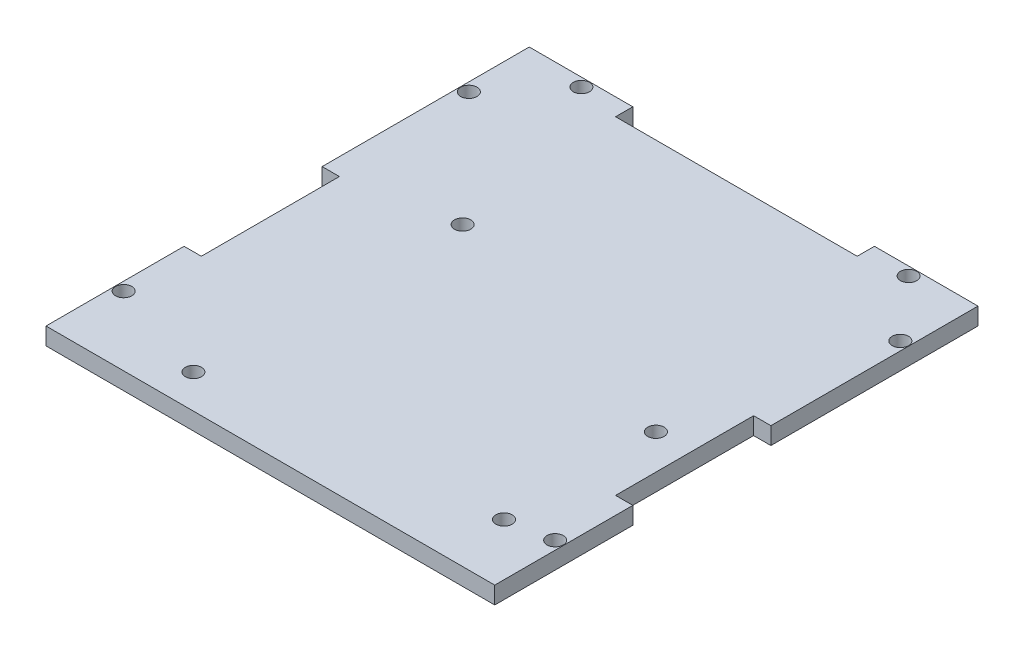
SolidWorks part; units mm, degrees
ref_plane "Front Plane" through (0, 0, 0) normal (0, 0, 1) x (1, 0, 0)
ref_plane "Top Plane" through (0, 0, 0) normal (0, 1, 0) x (1, 0, 0)
ref_plane "Right Plane" through (0, 0, 0) normal (1, 0, 0) x (0, 0, -1)
sketch "Sketch1" plane through (0, 0, 0) normal (0, 1, 0) x (1, 0, 0)
  line L0 (-41.275, 0) -> (-36.3683, -11.7139)
  line L1 (-10.2051, 85.725) -> (10.2051, 85.725)
  line L3 (-41.275, 88.9) -> (-22.225, 88.9)
  line L4 (22.225, 88.9) -> (22.225, 85.725)
  line L5 (41.275, 50.8) -> (41.275, 88.9)
  line L6 (-41.275, 0) -> (-38.1, 0) construction
  line L7 (-41.275, 50.8) -> (-38.1, 50.8)
  line L8 (0, 63.5) -> (0, -63.5) construction
  line L9 (38.1, 50.8) -> (38.1, 25.4)
  line L10 (-38.1, 50.8) -> (-38.1, 25.4)
  line L11 (-41.275, 50.8) -> (-41.275, 88.9)
  line L12 (41.275, 50.8) -> (38.1, 50.8)
  line L13 (-22.225, 88.9) -> (-22.225, 85.725)
  line L14 (-22.225, 85.725) -> (-10.2051, 85.725)
  line L16 (41.275, 88.9) -> (22.225, 88.9)
  line L17 (-41.275, 0) -> (41.275, 0) construction
  line L18 (-38.1, 0) -> (-38.1, 25.4) construction
  line L19 (-38.1, 25.4) -> (-41.275, 25.4)
  line L21 (-41.275, 0) -> (-41.275, 25.4)
  line L22 (38.1, 25.4) -> (41.275, 25.4)
  line L23 (-38.1, 0) -> (-33.467, -10.4244) construction
  line L24 (41.275, 0) -> (41.275, 25.4)
  line L25 (33.467, -10.4244) -> (38.1, 0) construction
  line L26 (-36.3683, -11.7139) -> (-33.467, -10.4244) construction
  line L27 (41.275, 0) -> (36.3683, -11.7139)
  line L28 (36.3683, -11.7139) -> (33.467, -10.4244) construction
  line L29 (-17.858, -45.5446) -> (-12.7, -57.15) construction
  line L30 (-12.7, -57.15) -> (-15.6014, -58.4395) construction
  line L31 (-17.858, -45.5446) -> (-20.7593, -46.8341)
  line L32 (-15.6014, -58.4395) -> (-20.7593, -46.8341)
  line L33 (12.7, -57.15) -> (17.858, -45.5446) construction
  line L34 (-33.467, -10.4244) -> (-17.858, -45.5446)
  line L35 (-12.7, -57.15) -> (12.7, -57.15) construction
  line L36 (17.858, -45.5446) -> (33.467, -10.4244)
  line L38 (41.275, 69.85) -> (-41.275, 69.85) construction
  line L39 (12.7, -57.15) -> (15.6014, -58.4395) construction
  line L40 (17.858, -45.5446) -> (20.7593, -46.8341)
  line L41 (15.6014, -58.4395) -> (20.7593, -46.8341)
  line L42 (38.1, 0) -> (38.1, 25.4) construction
  line L43 (-15.6014, -58.4395) -> (-12.7, -60.325)
  line L44 (-5.08, -57.15) -> (-12.7, -57.15) construction
  line L45 (-5.08, -57.15) -> (-5.08, -60.325)
  line L46 (-5.08, -60.325) -> (-12.7, -60.325)
  line L47 (-12.7, -57.15) -> (-12.7, -60.325) construction
  line L48 (5.08, -57.15) -> (12.7, -57.15) construction
  line L49 (5.08, -57.15) -> (5.08, -60.325)
  line L50 (5.08, -60.325) -> (12.7, -60.325)
  line L51 (12.7, -57.15) -> (12.7, -60.325) construction
  line L52 (15.6014, -58.4395) -> (12.7, -60.325)
  line L53 (-5.08, -57.15) -> (5.08, -57.15)
  line L54 (33.467, -10.4244) -> (36.3683, -11.7139)
  line L55 (-33.467, -10.4244) -> (-36.3683, -11.7139)
  line L56 (10.2051, 85.725) -> (22.225, 85.725)
  point P0 (0, 0)
  point P1 (0, -57.15)
  dimension "D1" = 25.4
  dimension "D2" = 57.15
  dimension "D3" = 3.175
  dimension "D4" = 82.55
  dimension "D5" = 3.175
  dimension "D6" = 44.45
  dimension "D8" = 38.1
  dimension "D9" = 50.8
  dimension "D10" = 25.4
  dimension "D11" = 12.7
  dimension "D12" = 12.7
  dimension "D13" = 10.16
extrude "Boss-Extrude1" add sketch "Sketch1" along normal blind 3.175
sketch "Sketch2" plane through (0, 0, 0) normal (0, -1, 0) x (-1, 0, 0)
  line L0 (39.6875, 50.8) -> (39.6875, 88.9) construction
  line L1 (41.275, 50.8) -> (38.1, 50.8) construction
  line L2 (22.225, 88.9) -> (41.275, 88.9) construction
  line L3 (0, 85.725) -> (0, -57.15) construction
  line L6 (-5.08, -58.7375) -> (-15.1428, -58.7375) construction
  line L7 (5.08, -57.15) -> (-5.08, -57.15) construction
  line L8 (-22.225, 85.725) -> (22.225, 85.725) construction
  line L10 (22.225, 88.9) -> (41.275, 88.9) construction
  line L11 (39.6875, 25.4) -> (39.6875, -3.7899) construction
  line L12 (38.1, 25.4) -> (41.275, 25.4) construction
  line L15 (41.275, 0) -> (36.3683, -11.7139) construction
  line L18 (34.9176, -11.0691) -> (41.275, 3.235) construction
  line L23 (36.3683, -11.7139) -> (33.467, -10.4244) construction
  line L24 (41.275, 25.4) -> (41.275, 0) construction
  line L25 (19.3086, -46.1893) -> (13.0261, -60.325) construction
  line L26 (17.858, -45.5446) -> (20.7593, -46.8341) construction
  line L27 (12.7, -60.325) -> (5.08, -60.325) construction
  line L28 (5.08, -58.7375) -> (15.1428, -58.7375) construction
  line L29 (5.08, -60.325) -> (5.08, -57.15) construction
  line L30 (15.6014, -58.4395) -> (12.7, -60.325) construction
  line L31 (-19.3086, -46.1893) -> (-13.0261, -60.325) construction
  line L32 (-34.9176, -11.0691) -> (-41.275, 3.235) construction
  line L33 (-39.6875, 25.4) -> (-39.6875, -3.7899) construction
  line L34 (-39.6875, 50.8) -> (-39.6875, 88.9) construction
  circle A0 centre (39.6875, 76.2) radius 1.5
  circle A1 centre (-8.89, -58.7375) radius 1.5
  circle A2 centre (39.6875, 12.7) radius 1.5
  circle A3 centre (37.4966, -5.2664) radius 1.5
  circle A4 centre (16.7297, -51.992) radius 1.5
  circle A5 centre (8.89, -58.7375) radius 1.5
  circle A6 centre (-16.7297, -51.992) radius 1.5
  circle A7 centre (-37.4966, -5.2664) radius 1.5
  circle A8 centre (-39.6875, 12.7) radius 1.5
  circle A9 centre (-39.6875, 76.2) radius 1.5
  dimension "D1" = 3
  dimension "D4" = 6.35
  dimension "D6" = 3.81
  dimension "D2" = 3
  dimension "D3" = 12.7
  dimension "D5" = 6.35
  dimension "D7" = 12.7
extrude "Cut-Extrude1" cut sketch "Sketch2" against normal through all
sketch "Sketch4" plane through (0, 3.175, 0) normal (0, 1, 0) x (1, 0, 0)
  circle A0 centre (31.6815, 11.305) radius 1.5
  circle A1 centre (31.6815, 39.245) radius 1.5
  circle A2 centre (-20.3885, 6.225) radius 1.5
  circle A3 centre (-19.1185, 54.485) radius 1.5
  dimension "D1" = 3
  dimension "D2" = 3
  dimension "D3" = 3
  dimension "D4" = 3
extrude "Cut-Extrude3" cut sketch "Sketch4" against normal through all
sketch "Sketch5" plane through (0, 3.175, 0) normal (0, 1, 0) x (1, 0, 0)
  line L0 (-41.275, 25.4) -> (-41.275, 0) construction
  line L1 (41.275, 0) -> (-41.275, 0)
  line L2 (41.275, 0) -> (41.275, -60.325)
  line L3 (41.275, -60.325) -> (-41.275, -60.325)
  line L4 (-41.275, 0) -> (-41.275, -60.325)
  line L5 (-12.7, -60.325) -> (-5.08, -60.325) construction
extrude "Cut-Extrude4" cut sketch "Sketch5" against normal through all
sketch "Sketch6" plane through (0, 3.175, 0) normal (0, 1, 0) x (1, 0, 0)
  line L0 (-22.225, 87.3125) -> (-41.275, 87.3125) construction
  line L1 (-22.225, 85.725) -> (-22.225, 88.9) construction
  line L2 (-41.275, 88.9) -> (-41.275, 50.8) construction
  line L3 (22.225, 87.3125) -> (41.275, 87.3125) construction
  line L4 (22.225, 88.9) -> (22.225, 85.725) construction
  line L5 (41.275, 50.8) -> (41.275, 88.9) construction
  circle A0 centre (-30.099, 87.3125) radius 1.5
  circle A1 centre (30.099, 87.3125) radius 1.5
  dimension "D1" = 3
  dimension "D2" = 3
  dimension "D3" = 7.874
  dimension "D4" = 7.874
extrude "Cut-Extrude5" cut sketch "Sketch6" against normal through all
